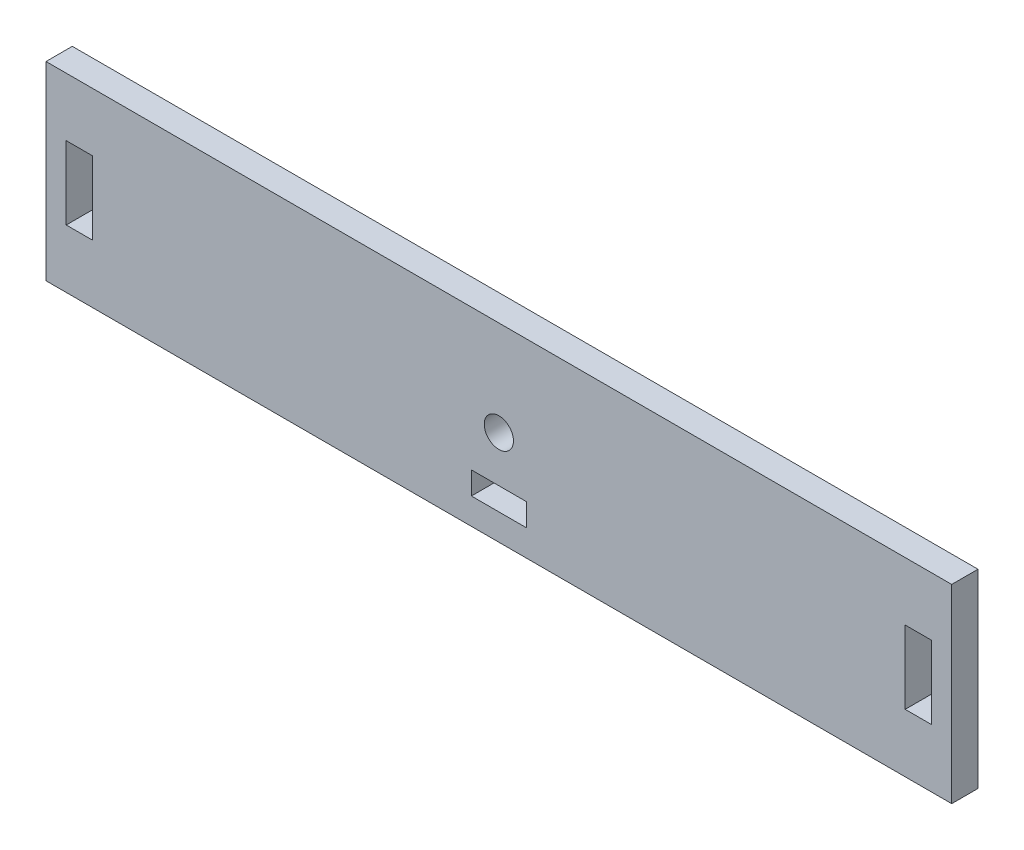
SolidWorks part; units mm, degrees
ref_plane "Front Plane" through (0, 0, 0) normal (0, 0, 1) x (1, 0, 0)
ref_plane "Top Plane" through (0, 0, 0) normal (0, 1, 0) x (1, 0, 0)
ref_plane "Right Plane" through (0, 0, 0) normal (1, 0, 0) x (0, 0, -1)
sketch "Sketch1" plane through (0, 0, 0) normal (0, 0, 1) x (1, 0, 0)
  line L0 (620, -65) -> (0, -65) construction
  line L1 (0, 0) -> (620, 0)
  line L2 (0, 0) -> (0, -130)
  line L3 (0, -130) -> (620, -130)
  line L4 (620, 0) -> (620, -130)
  line L5 (310, 0) -> (310, -130) construction
  line L6 (31.8563, -90) -> (13.8563, -90)
  line L7 (291.1922, -96.5005) -> (328.8078, -96.5005)
  line L8 (291.1922, -96.5005) -> (291.1922, -112)
  line L9 (291.1922, -112) -> (328.8078, -112)
  line L10 (328.8078, -96.5005) -> (328.8078, -112)
  line L11 (291.1922, -96.5005) -> (328.8078, -112) construction
  line L12 (291.1922, -112) -> (328.8078, -96.5005) construction
  line L13 (588.1437, -40) -> (606.1437, -40)
  line L14 (588.1437, -40) -> (588.1437, -90)
  line L15 (588.1437, -90) -> (606.1437, -90)
  line L16 (606.1437, -40) -> (606.1437, -90)
  line L17 (588.1437, -40) -> (606.1437, -90) construction
  line L18 (588.1437, -90) -> (606.1437, -40) construction
  line L19 (13.8563, -40) -> (13.8563, -90)
  line L20 (31.8563, -40) -> (13.8563, -40)
  line L21 (31.8563, -40) -> (31.8563, -90)
  circle A0 centre (310, -65) radius 10
  point P11 (310, -104.2502)
  point P16 (597.1437, -65)
  dimension "D3" = 18
  dimension "D1" = 620
  dimension "D2" = 130
  dimension "D4" = 50
  dimension "D5" = 18
extrude "Boss-Extrude1" add sketch "Sketch1" along normal blind 18
